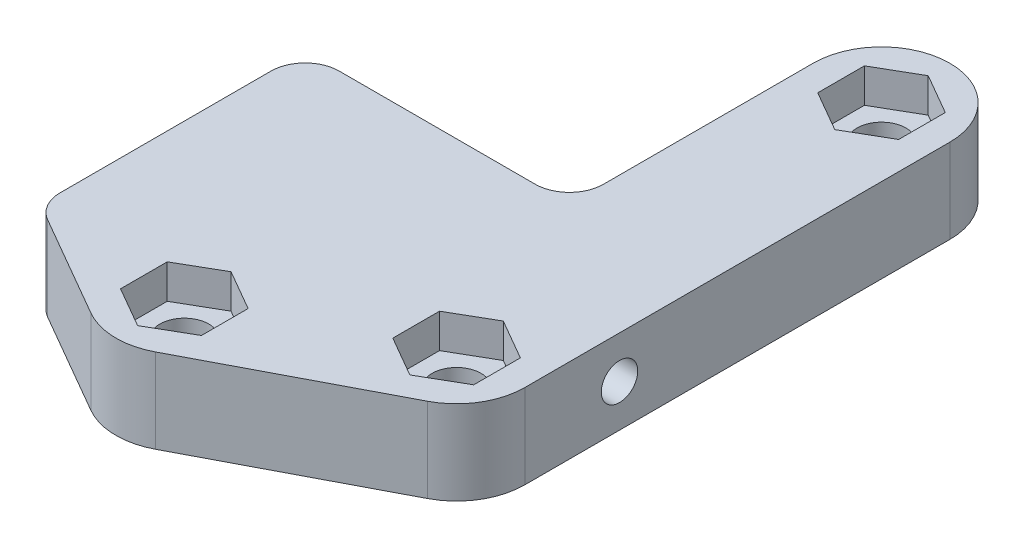
SolidWorks part; units mm, degrees
ref_plane "Front Plane" through (0, 0, 0) normal (0, 0, 1) x (1, 0, 0)
ref_plane "Top Plane" through (0, 0, 0) normal (0, 1, 0) x (1, 0, 0)
ref_plane "Right Plane" through (0, 0, 0) normal (1, 0, 0) x (0, 0, -1)
sketch "Sketch2" plane through (0, 0, 0) normal (0, 1, 0) x (1, 0, 0)
  line L0 (-11.5, -22.6506) -> (11.5, -22.6506) construction
  line L1 (0, -22.6506) -> (0, 22.6506) construction
  line L2 (-11.5, -22.6506) -> (-11.5, 22.6506) construction
  line L3 (-11.5, 22.6506) -> (11.5, 22.6506) construction
  line L4 (-13.5, -25.9846) -> (-3, -32.0468)
  line L5 (2.7777, -32.1689) -> (18.4777, -23.9689)
  line L6 (21.7, -18.6506) -> (21.7, 18.6506)
  line L7 (1.8518, -30.3962) -> (17.5518, -22.1962) construction
  line L8 (11.5, -22.6506) -> (11.5, 22.6506) construction
  line L9 (11.5, 22.6506) -> (15.7, 22.6506) construction
  line L10 (19.7, -18.6506) -> (19.7, 18.6506) construction
  line L11 (-11.5, -22.6506) -> (-11.5, -24.8299) construction
  line L12 (-11.5, -24.8299) -> (-2, -30.3147) construction
  line L13 (0, -26.8506) -> (0, -22.6506) construction
  line L14 (15.7, -18.6506) -> (11.5, -18.6506) construction
  line L15 (11.5, 0) -> (19.7, 0) construction
  line L16 (11.5, 24.6506) -> (15.7, 24.6506)
  line L17 (-13.5, 24.6506) -> (11.5, 24.6506)
  line L18 (-13.5, -22.6506) -> (-13.5, 24.6506)
  line L19 (-13.5, -22.6506) -> (-13.5, -25.9846)
  arc A0 (-2, -30.3147) -> (1.8518, -30.3962) centre (0, -26.8506) ccw construction
  circle A1 centre (0, -26.8506) radius 2.15
  arc A2 (17.5518, -22.1962) -> (19.7, -18.6506) centre (15.7, -18.6506) ccw construction
  arc A3 (15.7, 22.6506) -> (19.7, 18.6506) centre (15.7, 18.6506) cw construction
  circle A4 centre (15.7, -18.6506) radius 2.15
  circle A5 centre (15.7, 18.6506) radius 2.15
  arc A6 (-3, -32.0468) -> (2.7777, -32.1689) centre (0, -26.8506) ccw
  arc A7 (18.4777, -23.9689) -> (21.7, -18.6506) centre (15.7, -18.6506) ccw
  arc A8 (15.7, 24.6506) -> (21.7, 18.6506) centre (15.7, 18.6506) cw
  point P3 (0, 0)
  dimension "D3" = 4
  dimension "D4" = 4.3
  dimension "D1" = 45.3013
  dimension "D2" = 23
  dimension "D5" = 2.1793
  dimension "D6" = 4.2
  dimension "D7" = 2
extrude "Boss-Extrude1" add sketch "Sketch2" along normal blind 7.4
sketch "Sketch3" plane through (21.7, 0, 0) normal (-1, 0, 0) x (0, 0, 1)
  line L0 (10.3494, 7.4) -> (10.3494, 0) construction
  line L2 (-24.6506, 7.4) -> (25.9846, 7.4) construction
  line L5 (-24.6506, 0) -> (25.9846, 0) construction
  line L6 (-24.6506, 7.4) -> (-24.6506, 0) construction
  circle A0 centre (10.3494, 3.7) radius 1.6
  point P9 (10.3494, 3.7)
  dimension "D1" = 3.2
  dimension "D2" = 35
extrude "Cut-Extrude4" cut sketch "Sketch3" against normal through all and the other way through all
sketch "Sketch4" plane through (0, 7.4, 0) normal (0, -1, 0) x (1, 0, 0)
  line L1 (0, 22.7514) -> (3.55, 24.801)
  line L2 (3.55, 24.801) -> (3.55, 28.9002)
  line L3 (3.55, 28.9002) -> (0, 30.9498)
  line L4 (0, 30.9498) -> (-3.55, 28.9002)
  line L5 (-3.55, 28.9002) -> (-3.55, 24.801)
  line L6 (-3.55, 24.801) -> (0, 22.7514)
  line L7 (15.7, 14.5514) -> (19.25, 16.601)
  line L8 (19.25, 16.601) -> (19.25, 20.7002)
  line L9 (19.25, 20.7002) -> (15.7, 22.7498)
  line L10 (15.7, 22.7498) -> (12.15, 20.7002)
  line L11 (12.15, 20.7002) -> (12.15, 16.601)
  line L12 (12.15, 16.601) -> (15.7, 14.5514)
  line L13 (12.15, -20.7002) -> (15.7, -22.7498)
  line L14 (15.7, -22.7498) -> (19.25, -20.7002)
  line L15 (19.25, -20.7002) -> (19.25, -16.601)
  line L16 (19.25, -16.601) -> (15.7, -14.5514)
  line L17 (15.7, -14.5514) -> (12.15, -16.601)
  line L18 (12.15, -16.601) -> (12.15, -20.7002)
  circle A0 centre (0, 26.8506) radius 3.55 construction
  circle A1 centre (15.7, 18.6506) radius 3.55 construction
  circle A2 centre (15.7, -18.6506) radius 3.55 construction
  dimension "D1" = 7.1
extrude "Cut-Extrude1" cut sketch "Sketch4" along normal blind 3
sketch "Sketch5" plane through (0, 7.4, 0) normal (0, 1, 0) x (1, 0, 0)
  line L0 (-13.5, -8.7494) -> (-13.5, -11.9494) construction
  line L1 (-13.5, -8.7494) -> (-13.5, -11.9494) construction
  line L2 (-13.5, 24.6506) -> (-13.5, -2.7494)
  line L3 (-13.5, 24.6506) -> (-13.5, -25.9846) construction
  line L4 (-13.5, 24.6506) -> (15.7, 24.6506)
  line L5 (15.7, 24.6506) -> (-13.5, 24.6506) construction
  line L7 (21.7, -18.6506) -> (21.7, 18.6506) construction
  line L8 (-13.5, -8.7494) -> (21.7, -8.7494) construction
  line L9 (-13.5, -8.7494) -> (-13.5, -11.9494) construction
  line L10 (-13.5, -11.9494) -> (21.7, -11.9494) construction
  line L11 (21.7, -8.7494) -> (21.7, -11.9494) construction
  line L12 (9.7, 18.6506) -> (9.7, -2.7494)
  line L13 (9.7, -2.7494) -> (-13.5, -2.7494)
  arc A0 (15.7, 24.6506) -> (9.7, 18.6506) centre (15.7, 18.6506) ccw
  dimension "D1" = 6
extrude "Cut-Extrude5" cut sketch "Sketch5" against normal through all
fillet "Fillet1" radius 3 3 edges at (-13.5, 3.7, 25.9846) (9.7, 3.7, 2.7494) (-13.5, 3.7, 2.7494)
